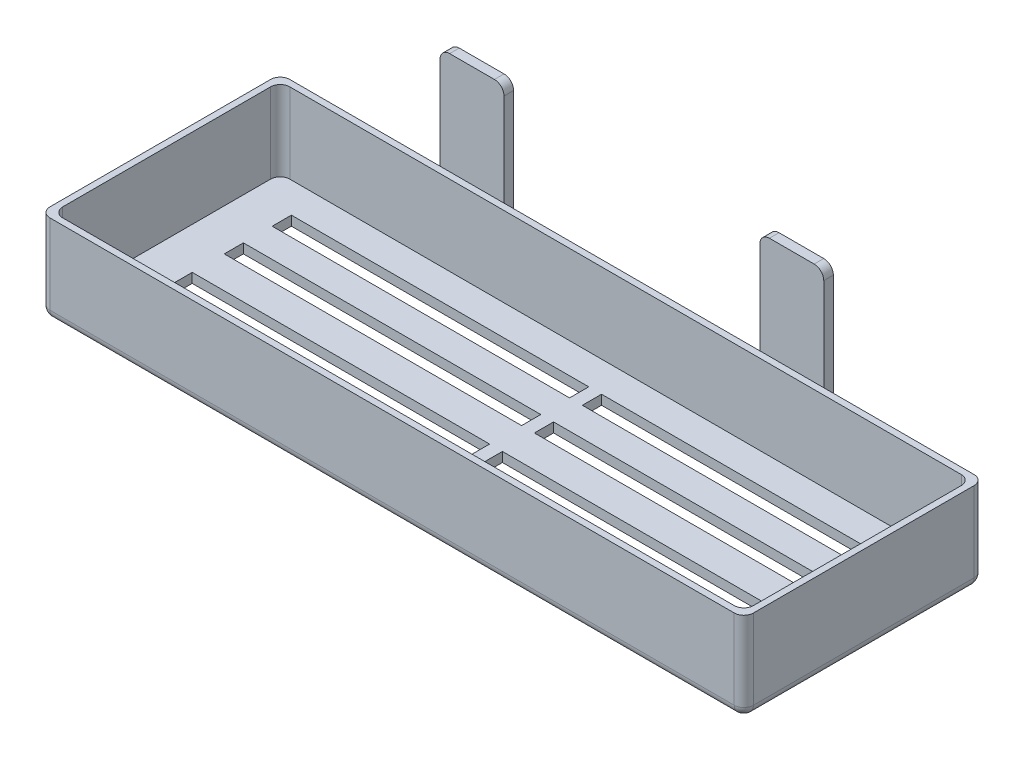
SolidWorks part; units mm, degrees
ref_plane "Vorderansicht" through (0, 0, 0) normal (0, 0, 1) x (1, 0, 0)
ref_plane "Draufsicht" through (0, 0, 0) normal (0, 1, 0) x (1, 0, 0)
ref_plane "Seitenansicht" through (0, 0, 0) normal (1, 0, 0) x (0, 0, -1)
sketch "Skizze1" plane through (0, 0, 0) normal (0, 1, 0) x (1, 0, 0)
  line L0 (-110, 37.5) -> (-110, -37.5)
  line L1 (-110, -37.5) -> (110, -37.5)
  line L2 (110, -37.5) -> (110, 37.5)
  line L3 (110, 37.5) -> (-110, 37.5)
  point P4 (0, 37.5)
  point P5 (110, 0)
  point P10 (-110, 0)
  point P11 (0, -37.5)
  dimension "D1" = 220
  dimension "D2" = 75
extrude "Aufsatz-Linear austragen1" add sketch "Skizze1" along normal blind 3
sketch "Skizze3" plane through (0, 0, 0) normal (0, 1, 0) x (1, 0, 0)
  line L0 (-40, 37.5) -> (-40, 40.5)
  line L1 (110, 37.5) -> (-110, 37.5) construction
  line L2 (-40, 40.5) -> (-60, 40.5)
  line L3 (-60, 40.5) -> (-60, 37.5)
  line L4 (-60, 37.5) -> (-40, 37.5)
  line L5 (40, 40.5) -> (60, 40.5)
  line L6 (60, 40.5) -> (60, 37.5)
  line L7 (60, 37.5) -> (40, 37.5)
  line L8 (40, 37.5) -> (40, 40.5)
  line L9 (110, -37.5) -> (110, 37.5) construction
  line L10 (-110, 37.5) -> (-110, -37.5) construction
  point P8 (40, 39)
  dimension "D1" = 20
  dimension "D2" = 3
  dimension "D3" = 80
  dimension "D4" = 50
  dimension "D5" = 50
extrude "Aufsatz-Linear austragen3" add sketch "Skizze3" along normal blind 60 contours L8 L7 L6 L5 | L2 L3 L4 L0
sketch "Skizze4" plane through (0, 3, 0) normal (0, 1, 0) x (1, 0, 0)
  line L8 (110, 37.5) -> (110, -37.5)
  line L9 (110, -37.5) -> (-110, -37.5)
  line L10 (-110, -37.5) -> (-110, 37.5)
  line L11 (-110, 37.5) -> (110, 37.5)
  line L16 (108, 35.5) -> (60, 35.5)
  line L17 (60, 35.5) -> (40, 35.5)
  line L18 (40, 35.5) -> (-40, 35.5)
  line L19 (-40, 35.5) -> (-60, 35.5)
  line L20 (-60, 35.5) -> (-108, 35.5)
  line L21 (-108, 35.5) -> (-108, -35.5)
  line L22 (-108, -35.5) -> (108, -35.5)
  line L23 (108, -35.5) -> (108, 35.5)
  line L24 (108, 35.5) -> (60, 35.5)
  line L25 (60, 35.5) -> (40, 35.5)
  line L26 (40, 35.5) -> (-40, 35.5)
  line L27 (-40, 35.5) -> (-60, 35.5)
  line L28 (-60, 35.5) -> (-108, 35.5)
  line L29 (-108, 35.5) -> (-108, -35.5)
  line L30 (-108, -35.5) -> (108, -35.5)
  line L31 (108, -35.5) -> (108, 35.5)
  dimension "D1" = 2
extrude "Aufsatz-Linear austragen4" add sketch "Skizze4" along normal blind 25
sketch "Skizze5" plane through (0, 3, 0) normal (0, 1, 0) x (1, 0, 0)
  line L0 (-95, 20) -> (95, 20)
  line L1 (95, 20) -> (95, 26)
  line L2 (95, 26) -> (-95, 26)
  line L3 (-95, 26) -> (-95, 20)
  line L4 (-95, 11) -> (95, 11)
  line L5 (95, 11) -> (95, 5)
  line L6 (95, 5) -> (-95, 5)
  line L7 (-95, 5) -> (-95, 11)
  line L8 (95, -5) -> (-95, -5)
  line L9 (-95, -5) -> (-95, -11)
  line L10 (-95, -11) -> (95, -11)
  line L11 (95, -11) -> (95, -5)
  line L12 (95, -20) -> (-95, -20)
  line L13 (-95, -20) -> (-95, -26)
  line L14 (-95, -26) -> (95, -26)
  line L15 (95, -26) -> (95, -20)
  point P16 (0, 20)
  point P17 (0, 5)
  point P19 (0, -5)
  point P20 (0, -20)
  dimension "D1" = 6
  dimension "D2" = 190
  dimension "D3" = 20
  dimension "D4" = 5
  dimension "D5" = 5
  dimension "D6" = 20
extrude "Schnitt-Linear austragen1" cut sketch "Skizze5" against normal through all
sketch "Skizze6" plane through (0, 3, 0) normal (0, 1, 0) x (1, 0, 0)
  line L0 (-2, 26) -> (2, 26)
  line L1 (95, 26) -> (-95, 26) construction
  line L2 (2, 26) -> (2, -26)
  line L3 (-95, -26) -> (95, -26) construction
  line L4 (2, -26) -> (-2, -26)
  line L5 (-2, -26) -> (-2, 26)
  point P4 (0, 26)
  dimension "D1" = 4
extrude "Aufsatz-Linear austragen5" add sketch "Skizze6" against normal through all
fillet "Verrundung1" radius 3 4 edges at (-60, 60, -39) (-40, 60, -39) (40, 60, -39) (60, 60, -39)
fillet "Verrundung2" radius 3 8 edges at (108, 15.5, -35.5) (-108, 15.5, -35.5) (-108, 15.5, 35.5) (108, 15.5, 35.5) (110, 14, -37.5) (110, 14, 37.5) (-110, 14, 37.5) (-110, 14, -37.5)
fillet "Verrundung3" radius 3 9 edges at (-110, 0, 0) (83.5, 0, -37.5) (110, 0, 0) (0, 0, 37.5) (109.1213, 0, 36.6213) (109.1213, 0, -36.6213) (-109.1213, 0, 36.6213) (-109.1213, 0, -36.6213) (-83.5, 0, -37.5)
fillet "Verrundung4" radius 3 1 edges at (0, 0, -37.5)
